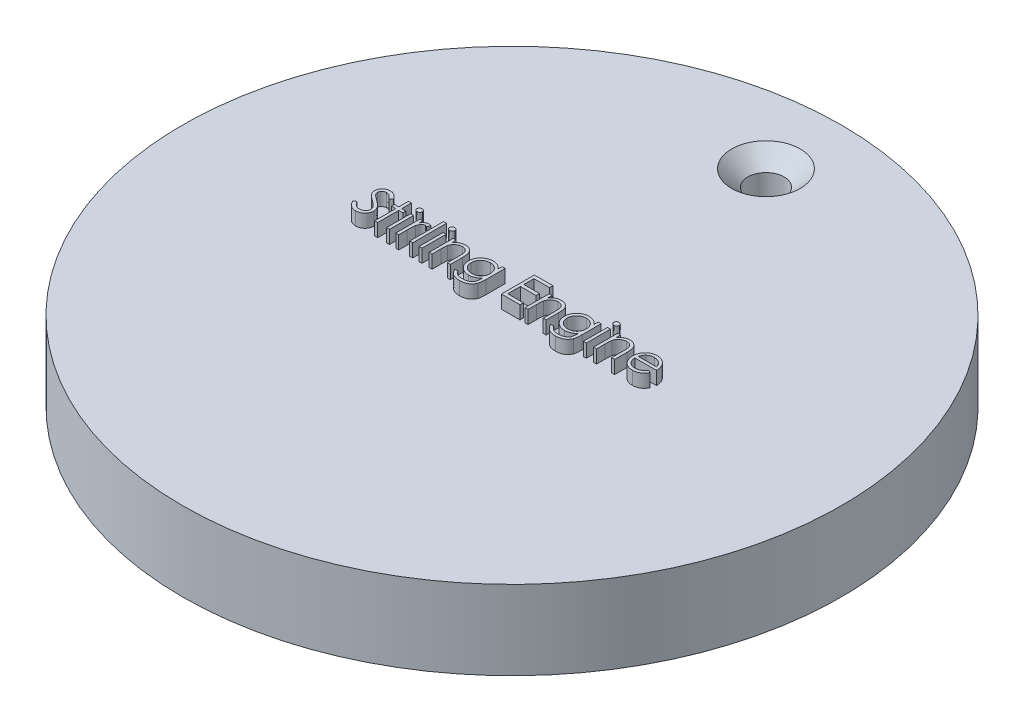
SolidWorks part; units mm, degrees
ref_plane "Front Plane" through (0, 0, 0) normal (0, 0, 1) x (1, 0, 0)
ref_plane "Top Plane" through (0, 0, 0) normal (0, 1, 0) x (1, 0, 0)
ref_plane "Right Plane" through (0, 0, 0) normal (1, 0, 0) x (0, 0, -1)
sketch "Sketch1" plane through (0, 0, 0) normal (0, 1, 0) x (1, 0, 0)
  circle A0 centre (0, 0) radius 50
  dimension "D1" = 100
extrude "Boss-Extrude1" add sketch "Sketch1" along normal blind 12
hole_wizard "CSK for M5 Countersunk Flat Head Screw1" positions "Sketch2" profile "Sketch3" countersink size "M5" standard "ISO"
sketch "Sketch2" plane through (0, 12, 0) normal (0, 1, 0) x (1, 0, 0)
  point P0 (0, 38.5286)
sketch "Sketch3" plane through (0, 12, -38.5286) normal (1, 0, 0) x (0, 0, 1)
  line L0 (0, 0) -> (0, 15)
  line L1 (0, 15) -> (2.75, 13.3476)
  line L2 (2.75, 13.3476) -> (2.75, 2.45)
  line L3 (2.75, 2.45) -> (5.2, 0)
  line L5 (5.2, 0) -> (0, 0)
  line L6 (-2.75, 2.45) -> (-5.2, 0) construction
  line L10 (0, 15) -> (-2.75, 13.3476) construction
  line L11 (0, -6.35) -> (0, 107.95) construction
  dimension "Hole Dia." = 5.5
  dimension "Hole Depth" = 15
  dimension "Near C'Sink Dia." = 10.4
  dimension "Near C'Sink Angle" = 90
  dimension "Drill Angle" = 118
sketch "Sketch4" plane through (0, 12, 0) normal (0, 1, 0) x (1, 0, 0)
  line L0 (-34.8756, 0) -> (30.7402, 0) construction
  text T0 "     Stirling Engine" font "Century Gothic" height 5
extrude "Boss-Extrude2" add sketch "Sketch4" along normal blind 2
